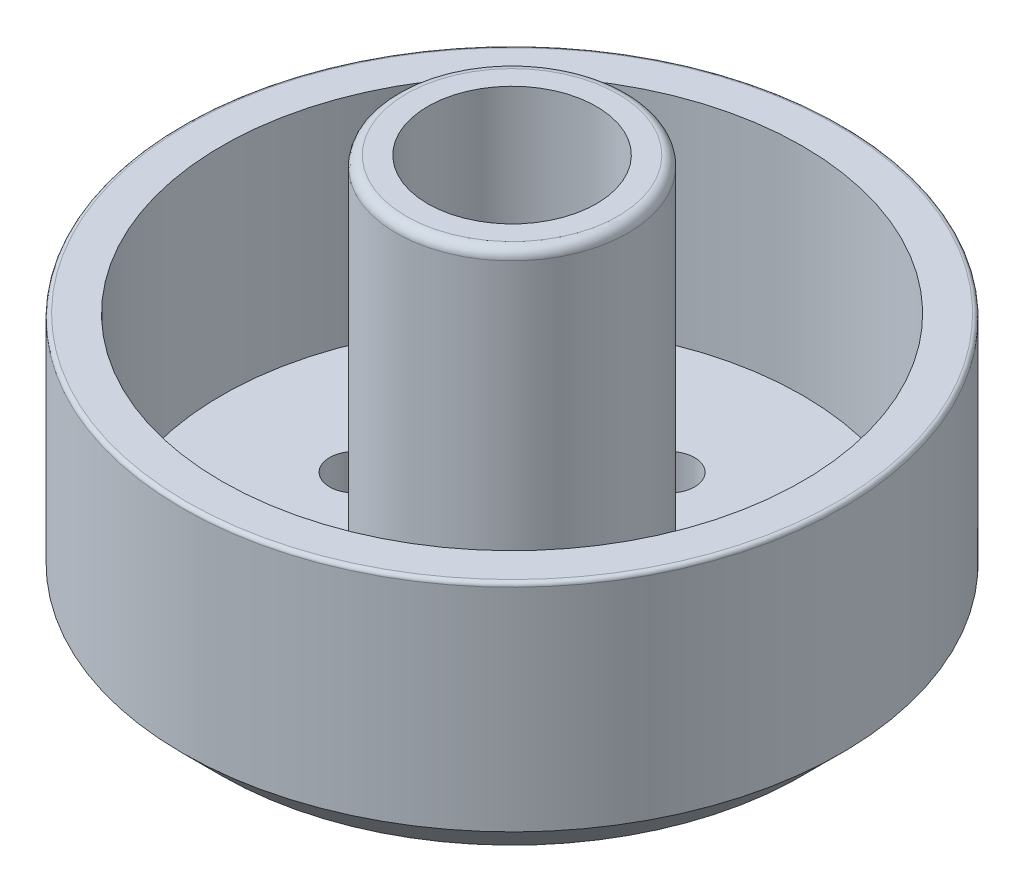
SolidWorks part; units mm, degrees
ref_plane "前视基准面" through (0, 0, 0) normal (0, 0, 1) x (1, 0, 0)
ref_plane "上视基准面" through (0, 0, 0) normal (0, 1, 0) x (1, 0, 0)
ref_plane "右视基准面" through (0, 0, 0) normal (1, 0, 0) x (0, 0, -1)
sketch "草图1" plane through (0, 0, 0) normal (0, 1, 0) x (1, 0, 0)
  circle A0 centre (0, 0) radius 16.8
  circle A1 centre (0, 8) radius 1.3
  circle A2 centre (8, 0) radius 1.3
  circle A3 centre (0, -8) radius 1.3
  circle A4 centre (-8, 0) radius 1.3
  circle A5 centre (0, 0) radius 4.3
  point P14 (0, 0)
  dimension "D1" = 33.6
  dimension "D2" = 2.6
  dimension "D5" = 8.6
  dimension "D3" = 8
  dimension "D4" = 4
extrude "凸台-拉伸1" add sketch "草图1" along normal blind 13
sketch "草图2" plane through (0, 13, 0) normal (0, 1, 0) x (1, 0, 0)
  circle A2 centre (0, 0) radius 16.8 construction
  circle A3 centre (0, 0) radius 16.8 construction
  circle A4 centre (0, 0) radius 14.8
  dimension "D1" = 2
extrude "切除-拉伸1" cut sketch "草图2" against normal offset from surface (11 mm away) 2 up to face at (0, 0, 16.8)
fillet "圆角1" radius 0.2 1 edges at (0, 13, 16.8)
sketch "草图3" plane through (0, 2, 0) normal (0, 1, 0) x (1, 0, 0)
  circle A0 centre (0, 0) radius 5.9
  circle A1 centre (0, 0) radius 4.3 construction
  circle A2 centre (0, 0) radius 4.3
  dimension "D1" = 11.8
extrude "凸台-拉伸2" add sketch "草图3" along normal blind 18
fillet "圆角2" radius 0.5 1 edges at (0, 20, 5.9)
ref_plane "基准面1" through (0, 0, 0) normal (0, 0, 1) x (1, 0, 0)
sketch "草图4" plane through (0, 0, 0) normal (0, 0, 1) x (1, 0, 0)
  line L0 (-16.8, 2) -> (-14.8, 0)
  line L1 (-16.8, 12.8) -> (-16.8, 0) construction
  line L2 (-16.8, 0) -> (16.8, 0) construction
  line L3 (-14.8, 0) -> (-16.8, 0)
  line L4 (-16.8, 0) -> (-16.8, 2)
  line L5 (0, 23.7746) -> (0, -10.6425) construction
  dimension "D1" = 45
  dimension "D2" = 2
revolve "切除-旋转1" cut sketch "草图4" angle 360 about L5
